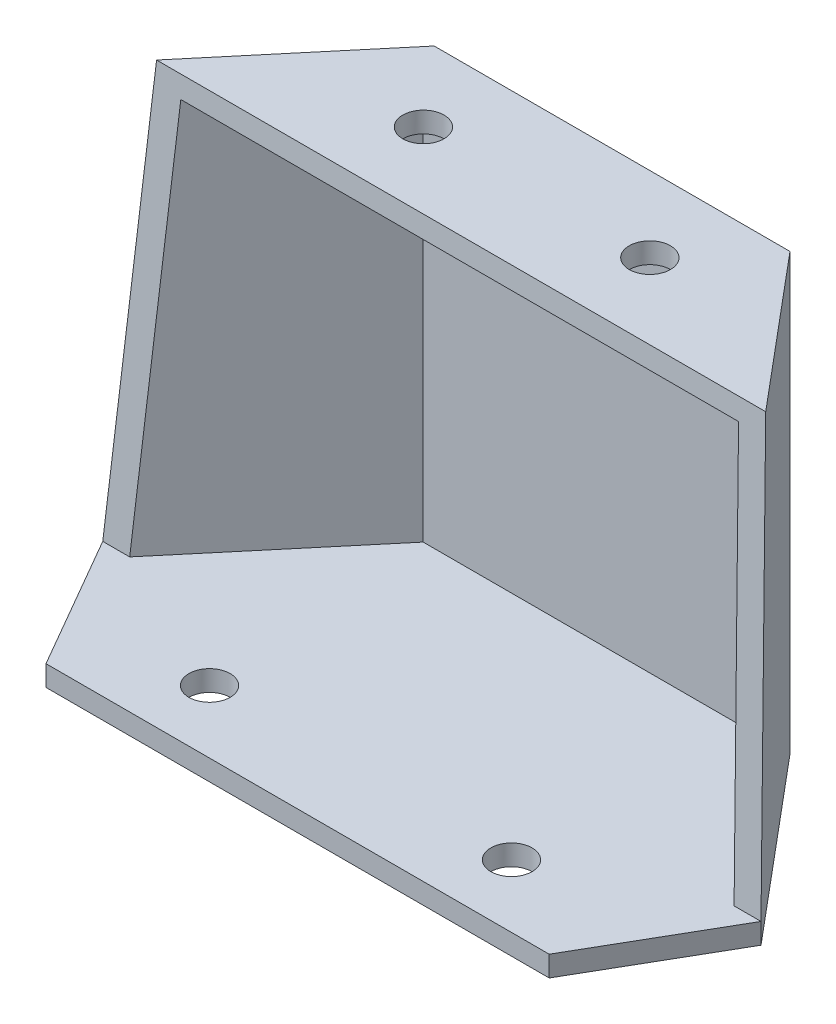
SolidWorks part; units mm, degrees
ref_plane "前视基准面" through (0, 0, 0) normal (0, 0, 1) x (1, 0, 0)
ref_plane "上视基准面" through (0, 0, 0) normal (0, 1, 0) x (1, 0, 0)
ref_plane "右视基准面" through (0, 0, 0) normal (1, 0, 0) x (0, 0, -1)
sketch "草图1" plane through (0, 0, 0) normal (0, 1, 0) x (1, 0, 0)
  line L0 (0, 0) -> (0, 152.5) construction
  line L1 (122, 0) -> (-122, 0)
  line L2 (-122, 0) -> (-159.5924, 65.1119)
  line L3 (-159.5924, 65.1119) -> (-86.265, 152.5)
  line L4 (-86.265, 152.5) -> (86.265, 152.5)
  line L5 (159.5924, 65.1119) -> (86.265, 152.5)
  line L6 (122, 0) -> (159.5924, 65.1119)
  dimension "D1" = 244
  dimension "D2" = 30
  dimension "D3" = 40
  dimension "D4" = 152.5
  dimension "D5" = 172.53
extrude "凸台-拉伸1" add sketch "草图1" along normal blind 211
shell "抽壳1" thickness 10
sketch "草图2" plane through (0, 0, 0) normal (1, 0, 0) x (0, 0, -1)
  line L0 (79.3, 211) -> (65.1119, 10)
  line L1 (65.1119, 211) -> (152.5, 211) construction
  line L2 (65.1119, 211) -> (65.1119, 0) construction
  line L3 (65.1119, 0) -> (152.5, 0) construction
  line L4 (79.3, 211) -> (0, 211)
  line L5 (0, 211) -> (0, 10)
  line L6 (0, 211) -> (0, 0) construction
  line L7 (0, 10) -> (65.1119, 10)
  dimension "D1" = 10
  dimension "D2" = 73.2
extrude "切除-拉伸1" cut sketch "草图2" against normal through all both and the other way through all
sketch "草图3" plane through (0, 211, 0) normal (0, 1, 0) x (1, 0, 0)
  line L0 (0, 0) -> (0, 152.5) construction
  line L1 (86.265, 152.5) -> (-86.265, 152.5) construction
  circle A0 centre (-54.9, 115.9) radius 10
  circle A1 centre (54.9, 115.9) radius 10
  dimension "D1" = 20
  dimension "D2" = 109.8
  dimension "D3" = 36.6
extrude "切除-拉伸2" cut sketch "草图3" against normal up to next
sketch "草图4" plane through (0, 10, 0) normal (0, 1, 0) x (1, 0, 0)
  line L0 (0, 0) -> (0, 79.3) construction
  line L1 (-122, 0) -> (122, 0) construction
  line L2 (-147.6871, 79.3) -> (147.6871, 79.3) construction
  circle A0 centre (-73.2, 30.5) radius 10
  circle A1 centre (73.2, 30.5) radius 10
  dimension "D1" = 20
  dimension "D2" = 30.5
  dimension "D3" = 146.4
extrude "切除-拉伸3" cut sketch "草图4" against normal up to next
